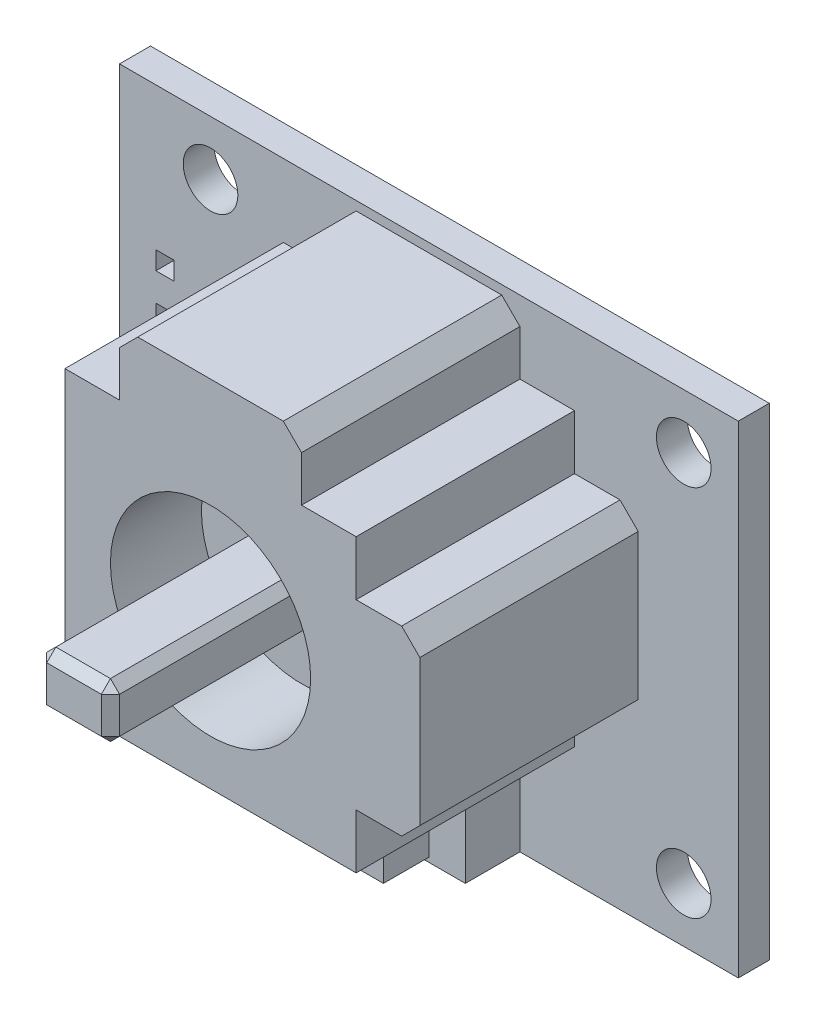
SolidWorks part; units mm, degrees
ref_plane "Спереди" through (0, 0, 0) normal (0, 0, 1) x (1, 0, 0)
ref_plane "Сверху" through (0, 0, 0) normal (0, 1, 0) x (1, 0, 0)
ref_plane "Справа" through (0, 0, 0) normal (1, 0, 0) x (0, 0, -1)
sketch "Эскиз1" plane through (0, 0, 0) normal (0, 0, 1) x (1, 0, 0)
  line L1 (-17, 13.25) -> (17, 13.25)
  line L2 (-17, 13.25) -> (-17, -13.25)
  line L3 (-17, -13.25) -> (17, -13.25)
  line L4 (17, 13.25) -> (17, -13.25)
  line L5 (-17, 13.25) -> (17, -13.25) construction
  line L6 (-17, -13.25) -> (17, 13.25) construction
  point P0 (0, 0)
  dimension "D1" = 34
  dimension "D2" = 26.5
extrude "Бобышка-Вытянуть1" add sketch "Эскиз1" along normal blind 1.7
sketch "Эскиз2" plane through (0, 0, 1.7) normal (0, 0, 1) x (1, 0, 0)
  line L0 (17, 13.25) -> (-17, 13.25) construction
  line L1 (-8, 9.25) -> (8, 9.25)
  line L2 (-8, 9.25) -> (-8, -6.75)
  line L3 (-8, -6.75) -> (8, -6.75)
  line L4 (8, 9.25) -> (8, -6.75)
  line L5 (-8, 9.25) -> (8, -6.75) construction
  line L6 (-8, -6.75) -> (8, 9.25) construction
  point P0 (0, 0)
  dimension "D1" = 16
  dimension "D2" = 16
  dimension "D3" = 4
extrude "Бобышка-Вытянуть2" add sketch "Эскиз2" along normal blind 12
sketch "Эскиз3" plane through (0, 0, 1.7) normal (0, 0, 1) x (1, 0, 0)
  line L0 (-8, -6.75) -> (8, -6.75) construction
  line L1 (-5, -6.75) -> (5, -6.75)
  line L2 (-5, -6.75) -> (-5, -13.25)
  line L3 (-5, -13.25) -> (5, -13.25)
  line L4 (5, -6.75) -> (5, -13.25)
  line L5 (-17, -13.25) -> (17, -13.25) construction
  line L6 (0, 3.165) -> (0, -11.6881) construction
  point P11 (0, -13.25)
  dimension "D1" = 10
extrude "Бобышка-Вытянуть3" add sketch "Эскиз3" along normal blind 3
sketch "Эскиз4" plane through (0, 0, 4.7) normal (0, 0, 1) x (1, 0, 0)
  line L0 (0, -13.25) -> (0, -6.75) construction
  line L1 (-5, -13.25) -> (5, -13.25) construction
  line L2 (-8, -6.75) -> (8, -6.75) construction
  line L3 (-5, -10) -> (5, -10) construction
  line L4 (-5, -6.75) -> (-5, -13.25) construction
  line L5 (5, -13.25) -> (5, -6.75) construction
  line L7 (-3, -7) -> (3, -7)
  line L8 (-3, -7) -> (-3, -13)
  line L9 (-3, -13) -> (3, -13)
  line L10 (3, -7) -> (3, -13)
  line L11 (-3, -7) -> (3, -13) construction
  line L12 (-3, -13) -> (3, -7) construction
  point P12 (0, -10)
  dimension "D1" = 6
  dimension "D2" = 6
extrude "Бобышка-Вытянуть4" add sketch "Эскиз4" along normal blind 2.5
sketch "Эскиз5" plane through (0, 0, 7.2) normal (0, 0, 1) x (1, 0, 0)
  line L0 (-3, -10) -> (3, -10) construction
  line L1 (-3, -7) -> (-3, -13) construction
  line L2 (3, -13) -> (3, -7) construction
  line L3 (0, -7) -> (0, -13) construction
  line L4 (3, -7) -> (-3, -7) construction
  line L5 (-3, -13) -> (3, -13) construction
  circle A0 centre (0, -10) radius 1.5532
extrude "Бобышка-Вытянуть5" add sketch "Эскиз5" along normal blind 0.5
sketch "Эскиз6" plane through (0, 0, 1.7) normal (0, 0, 1) x (1, 0, 0)
  line L0 (0, 9.25) -> (0, 15.6414) construction
  line L1 (8, 9.25) -> (-8, 9.25) construction
  line L2 (8, 1.25) -> (15.2236, 1.25) construction
  line L3 (-5, 12.75) -> (5, 12.75)
  line L4 (-5, 12.75) -> (-5, 9.25)
  line L5 (-5, 9.25) -> (5, 9.25)
  line L6 (5, 12.75) -> (5, 9.25)
  line L7 (-5, 12.75) -> (5, 9.25) construction
  line L8 (-5, 9.25) -> (5, 12.75) construction
  line L9 (8, -6.75) -> (8, 9.25) construction
  line L10 (8, -6.75) -> (8, 9.25) construction
  line L11 (8, 6.25) -> (11.5, 6.25)
  line L12 (8, 6.25) -> (8, -3.75)
  line L13 (8, -3.75) -> (11.5, -3.75)
  line L14 (11.5, 6.25) -> (11.5, -3.75)
  line L15 (8, 6.25) -> (11.5, -3.75) construction
  line L16 (8, -3.75) -> (11.5, 6.25) construction
  point P5 (0, 11)
  point P14 (9.75, 1.25)
  dimension "D1" = 3.5
  dimension "D2" = 10
  dimension "D3" = 10
  dimension "D4" = 3.5
extrude "Бобышка-Вытянуть6" add sketch "Эскиз6" along normal up to surface (12 mm away) up to face at (0, 1.25, 13.7)
chamfer "Фаска1" distance 1 angle 45 4 edges at (11.5, -3.75, 7.7) (11.5, 6.25, 7.7) (5, 12.75, 7.7) (-5, 12.75, 7.7)
sketch "Эскиз7" plane through (0, 0, 13.7) normal (0, 0, 1) x (1, 0, 0)
  line L0 (8, 9.25) -> (-8, -6.75) construction
  line L1 (-8, 9.25) -> (8, -6.75) construction
  circle A0 centre (0, 1.25) radius 5.5
  dimension "D1" = 11
extrude "Вырез-Вытянуть1" cut sketch "Эскиз7" against normal blind 5
sketch "Эскиз8" plane through (0, 0, 8.7) normal (0, 0, 1) x (1, 0, 0)
  line L1 (-2, 2.75) -> (2, 2.75)
  line L2 (-2, 2.75) -> (-2, -0.25)
  line L3 (-2, -0.25) -> (2, -0.25)
  line L4 (2, 2.75) -> (2, -0.25)
  line L5 (-2, 2.75) -> (2, -0.25) construction
  line L6 (-2, -0.25) -> (2, 2.75) construction
  point P2 (0, 1.25)
  dimension "D1" = 3
  dimension "D2" = 4
extrude "Бобышка-Вытянуть7" add sketch "Эскиз8" along normal blind 12.5
chamfer "Фаска2" distance 0.5 angle 45 12 edges at (0, 2.75, 8.7) (-2, 1.25, 8.7) (2, 1.25, 8.7) (-2, -0.25, 14.95) (0, -0.25, 8.7) (2, -0.25, 14.95) (0, -0.25, 21.2) (-2, 1.25, 21.2) (-2, 2.75, 14.95) (0, 2.75, 21.2) (2, 1.25, 21.2) (2, 2.75, 14.95)
sketch "Эскиз9" plane through (0, 0, 1.7) normal (0, 0, 1) x (1, 0, 0)
  line L0 (14, 13.25) -> (14, -13.25) construction
  line L1 (17, 13.25) -> (-17, 13.25) construction
  line L2 (5, -13.25) -> (17, -13.25) construction
  line L3 (17, -13.25) -> (17, 13.25) construction
  line L4 (17, 10.25) -> (-17, 10.25) construction
  line L5 (-17, 13.25) -> (-17, -13.25) construction
  line L6 (17, -10.25) -> (-17, -10.25) construction
  line L7 (-17, -13.25) -> (-5, -13.25) construction
  line L8 (-12, 13.25) -> (-12, -13.25) construction
  circle A0 centre (14, 10.25) radius 1.5
  circle A1 centre (14, -10.25) radius 1.5
  circle A2 centre (-12, 10.25) radius 1.5
  circle A3 centre (-12, -10.25) radius 1.5
  dimension "D1" = 3
  dimension "D2" = 3
  dimension "D6" = 3
  dimension "D7" = 3
  dimension "D3" = 3
  dimension "D4" = 3
  dimension "D5" = 3
  dimension "D8" = 5
extrude "Вырез-Вытянуть2" cut sketch "Эскиз9" against normal through all
sketch "Эскиз10" plane through (0, 0, 1.7) normal (0, 0, 1) x (1, 0, 0)
  line L0 (-14.5, 13.25) -> (-14.5, -13.25) construction
  line L1 (17, 13.25) -> (-17, 13.25) construction
  line L2 (-17, -13.25) -> (-5, -13.25) construction
  line L3 (-17, 13.25) -> (-17, -13.25) construction
  line L4 (-15, 2.8644) -> (-15, 1.8644)
  line L5 (-15, 5.4044) -> (-14, 5.4044)
  line L6 (-15, 5.4044) -> (-15, 4.4044)
  line L7 (-15, 4.4044) -> (-14, 4.4044)
  line L8 (-14, 5.4044) -> (-14, 4.4044)
  line L9 (-15, 5.4044) -> (-14, 4.4044) construction
  line L10 (-15, 4.4044) -> (-14, 5.4044) construction
  line L11 (-15, 2.8644) -> (-14, 2.8644)
  line L12 (-15, 1.8644) -> (-14, 1.8644)
  line L13 (-14, 2.8644) -> (-14, 1.8644)
  line L14 (-15, 0.3244) -> (-15, -0.6756)
  line L15 (-15, 0.3244) -> (-14, 0.3244)
  line L16 (-15, -0.6756) -> (-14, -0.6756)
  line L17 (-14, 0.3244) -> (-14, -0.6756)
  line L18 (-15, -2.2156) -> (-15, -3.2156)
  line L19 (-15, -2.2156) -> (-14, -2.2156)
  line L20 (-15, -3.2156) -> (-14, -3.2156)
  line L21 (-14, -2.2156) -> (-14, -3.2156)
  line L22 (-15, -4.7556) -> (-15, -5.7556)
  line L23 (-15, -4.7556) -> (-14, -4.7556)
  line L24 (-15, -5.7556) -> (-14, -5.7556)
  line L25 (-14, -4.7556) -> (-14, -5.7556)
  point P8 (-14.5, 4.9044)
  dimension "D1" = 2.5
  dimension "D2" = 1
  dimension "D3" = 1
  dimension "D4" = 5
extrude "Вырез-Вытянуть3" cut sketch "Эскиз10" against normal through all
